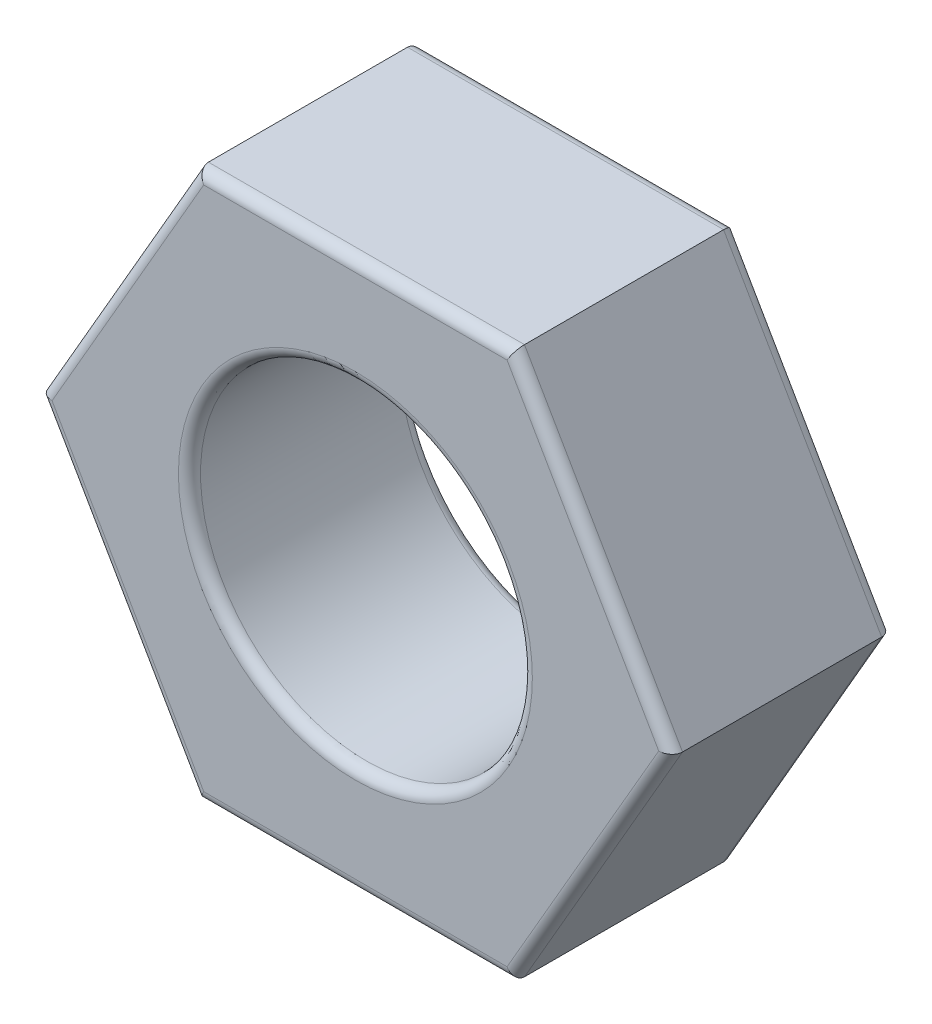
SolidWorks part; units mm, degrees
ref_plane "Front Plane" through (0, 0, 0) normal (0, 0, 1) x (1, 0, 0)
ref_plane "Top Plane" through (0, 0, 0) normal (0, 1, 0) x (1, 0, 0)
ref_plane "Right Plane" through (0, 0, 0) normal (1, 0, 0) x (0, 0, -1)
sketch "Sketch1" plane through (0, 0, 0) normal (0, 0, 1) x (1, 0, 0)
  line L1 (2.8579, 4.95) -> (-2.8579, 4.95)
  line L2 (-2.8579, 4.95) -> (-5.7158, 0)
  line L3 (-5.7158, 0) -> (-2.8579, -4.95)
  line L4 (-2.8579, -4.95) -> (2.8579, -4.95)
  line L5 (2.8579, -4.95) -> (5.7158, 0)
  line L6 (5.7158, 0) -> (2.8579, 4.95)
  circle A0 centre (0, 0) radius 4.95 construction
  circle A1 centre (0, 0) radius 3
  dimension "D2" = 6
  dimension "D1" = 9.9
extrude "Extrude1" add sketch "Sketch1" along normal blind 4
fillet "Fillet1" radius 0.2 14 edges at (-4.2868, 2.475, 4) (-4.2868, -2.475, 4) (3, 0, 0) (0, -4.95, 4) (3, 0, 4) (4.2868, -2.475, 4) (4.2868, 2.475, 4) (4.2868, -2.475, 0) (0, -4.95, 0) (-4.2868, -2.475, 0) (-4.2868, 2.475, 0) (0, 4.95, 4) (0, 4.95, 0) (4.2868, 2.475, 0)
